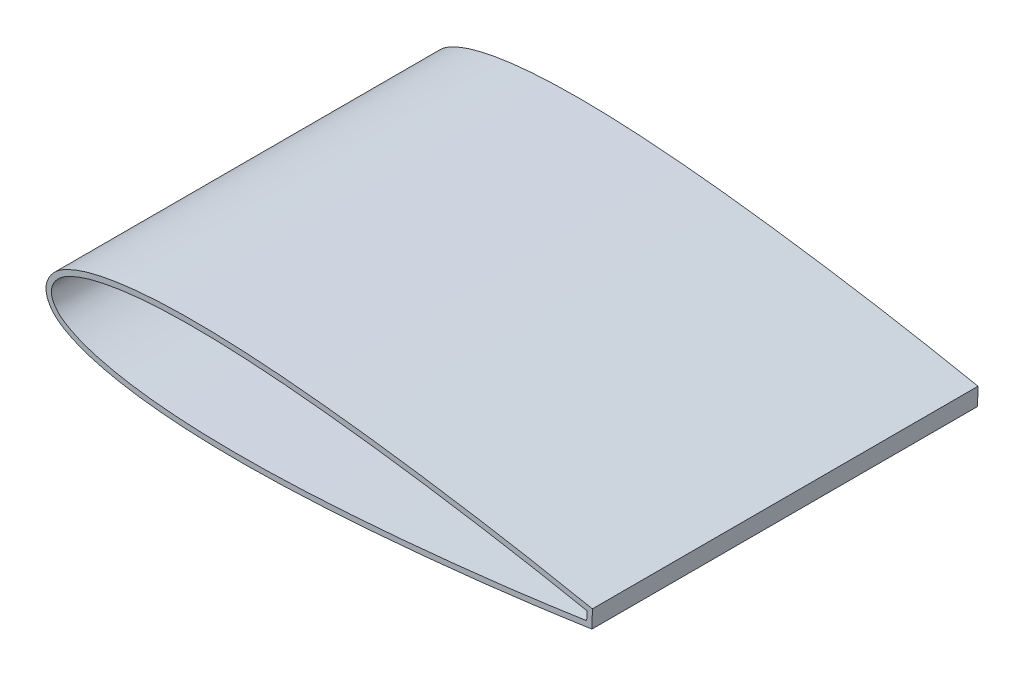
SolidWorks part; units mm, degrees
ref_plane "Alzado" through (0, 0, 0) normal (0, 0, 1) x (1, 0, 0)
ref_plane "Planta" through (0, 0, 0) normal (0, 1, 0) x (1, 0, 0)
ref_plane "Vista lateral" through (0, 0, 0) normal (1, 0, 0) x (0, 0, -1)
sketch "Croquis1" plane through (0, 0, 0) normal (0, 0, 1) x (1, 0, 0)
  line L1 (99.9588, -3.4209) -> (100, -1.7831)
  line L2 (100.9372, -4.2884) -> (101.0209, -0.9659)
  spline S0 degree 1 poles (101.0209, -0.9659) (100.9372, -4.2884) knots 0 0 1 1 construction
  spline S1 degree 3 poles (101.0209, -0.9659) (96.8153, -0.1329) (88.3989, 1.4983) (75.7013, 3.6191) (65.0923, 5.1744) (56.5758, 6.2611) (50.173, 6.9817) (43.7516, 7.5934) (37.3088, 8.062) (30.8435, 8.3521) (25.4356, 8.4019) (21.0964, 8.2838) (17.8368, 8.0987) (14.5726, 7.7994) (11.3002, 7.3497) (8.5784, 6.8084) (6.3964, 6.2318) (4.7455, 5.683) (3.1251, 4.9883) (1.5028, 4.12) (0.07, 2.8356) (-0.7762, 1.3315) (-1.0992, -0.0572) (-0.8465, -1.4604) (-0.077, -3.0052) (1.2893, -4.3602) (2.8658, -5.3089) (4.4492, -6.0843) (6.0704, -6.7154) (8.2207, -7.4011) (10.9117, -8.0788) (14.1574, -8.6925) (17.4024, -9.1557) (20.6486, -9.5046) (24.9763, -9.8409) (30.3799, -10.0633) (36.8516, -10.0989) (43.3098, -9.9551) (49.7538, -9.6673) (56.1848, -9.2698) (64.7452, -8.6131) (75.419, -7.5936) (88.2073, -6.1144) (96.6951, -4.9088) (100.9372, -4.2884) knots -0.007442 -0.007442 -0.007442 -0.007442 0.055988 0.119418 0.182849 0.214564 0.246279 0.277994 0.309709 0.341424 0.373139 0.388997 0.404855 0.420712 0.43657 0.452427 0.460356 0.468285 0.476214 0.484142 0.492071 0.496036 0.5 0.503964 0.507929 0.515858 0.523786 0.531715 0.539644 0.547573 0.56343 0.579288 0.595145 0.611003 0.626861 0.658576 0.690291 0.722006 0.753721 0.785436 0.817151 0.880582 0.944012 1.007442 1.007442 1.007442 1.007442
  spline S2 degree 3 poles (100, -1.7831) (95.8344, -0.958) (87.4933, 0.643) (74.9228, 2.7277) (62.3137, 4.5641) (49.6569, 6.0848) (39.0603, 6.9894) (30.5507, 7.3591) (24.1546, 7.4079) (18.8173, 7.1888) (14.5521, 6.79) (11.3582, 6.3445) (8.1856, 5.7066) (5.564, 4.9488) (3.5111, 4.0637) (2.0419, 3.2637) (0.599, 1.9526) (-0.279, -0.0779) (0.4957, -2.1499) (1.8708, -3.5321) (3.2979, -4.4049) (5.3036, -5.3922) (7.8838, -6.281) (11.0203, -7.0778) (14.1877, -7.6833) (18.4274, -8.2963) (23.747, -8.7837) (30.1374, -9.0568) (38.6548, -9.1158) (49.2835, -8.7455) (62.0009, -7.8637) (74.6864, -6.6642) (87.3459, -5.2146) (95.757, -4.0353) (99.9588, -3.4209) knots -0.003281 -0.003281 -0.003281 -0.003281 0.059629 0.122539 0.185449 0.24836 0.31127 0.342725 0.37418 0.405635 0.421362 0.43709 0.452817 0.468545 0.476409 0.484272 0.492136 0.5 0.507864 0.515728 0.523591 0.531455 0.547183 0.56291 0.578638 0.594365 0.62582 0.657275 0.68873 0.75164 0.814551 0.877461 0.940371 1.003281 1.003281 1.003281 1.003281
  dimension "D2" = 1
  dimension "D1" = 100
extrude "Saliente-Extruir1" add sketch "Croquis1" along normal blind 70
sketch "Croquis2" plane through (0, 0, 70) normal (0, 0, 1) x (1, 0, 0)
  line L0 (6.9696, 5.3388) -> (4.7355, 13.1426) construction
  line L1 (13.0976, 6.5801) -> (12.1874, 13.1292) construction
  line L2 (19.3249, 7.1769) -> (18.9088, 14.1748) construction
  line L3 (25.5786, 7.3722) -> (25.5327, 14.7723) construction
  line L4 (31.835, 7.2836) -> (32.0458, 13.7556) construction
  line L5 (38.085, 6.9832) -> (38.5713, 14.7812) construction
  line L6 (44.3249, 6.5168) -> (44.9854, 14.1724) construction
  line L7 (50.5535, 5.918) -> (51.1744, 11.8208) construction
  line L8 (56.7712, 5.2143) -> (57.5908, 11.9985) construction
  line L9 (62.9782, 4.4217) -> (63.8478, 10.901) construction
  line L10 (69.175, 3.5529) -> (70.2993, 11.2554) construction
  line L11 (75.362, 2.6168) -> (76.4898, 9.8261) construction
  line L12 (81.5391, 1.618) -> (82.5894, 7.9004) construction
  line L13 (87.7048, 0.5506) -> (88.9057, 7.2473) construction
  line L14 (93.275, -0.4778) -> (94.3912, 5.4138) construction
  line L15 (93.7641, -4.305) -> (94.4573, -9.3042) construction
  line L16 (87.5617, -5.1329) -> (88.3084, -10.9765) construction
  line L17 (81.3501, -5.8888) -> (81.9821, -11.3457) construction
  line L18 (75.1305, -6.5754) -> (75.5961, -10.9995) construction
  line L19 (68.9043, -7.1991) -> (69.4026, -12.4508) construction
  line L20 (62.6716, -7.7549) -> (63.088, -12.7548) construction
  line L21 (56.4326, -8.2342) -> (56.8686, -14.4627) construction
  line L22 (50.1874, -8.6241) -> (50.5085, -14.5151) construction
  line L23 (43.9365, -8.9087) -> (44.1623, -15.2248) construction
  line L24 (37.6811, -9.0605) -> (37.7711, -16.6006) construction
  line L25 (31.4239, -9.0461) -> (31.2647, -17.995) construction
  line L26 (25.1709, -8.8197) -> (24.6283, -18.4061) construction
  line L27 (18.935, -8.31) -> (17.9505, -17.2458) construction
  line L28 (12.7457, -7.4005) -> (10.6255, -18.5177) construction
  line L29 (6.6879, -5.8524) -> (3.2835, -15.8184) construction
  line L30 (1.247, -2.8692) -> (-5.2779, -9.0949) construction
  line L31 (0, 0) -> (-9.3368, 0.5427)
  line L32 (1.3855, 2.6331) -> (-4.9918, 9.3628) construction
  spline S0 degree 3 poles (1410.1565, 3729.758) (505.9884, -229.8774) (307.0725, -35.7726) (74.9228, 2.7277) (62.3137, 4.5641) (49.6569, 6.0848) (39.0603, 6.9894) (30.5507, 7.3591) (24.1546, 7.4079) (18.8173, 7.1888) (14.5521, 6.79) (11.3582, 6.3445) (8.1856, 5.7066) (5.564, 4.9488) (3.5111, 4.0637) (2.0419, 3.2637) (0.599, 1.9526) (-0.279, -0.0779) (0.4957, -2.1499) (1.8708, -3.5321) (3.2979, -4.4049) (5.3036, -5.3922) (7.8838, -6.281) (11.0203, -7.0778) (14.1877, -7.6833) (18.4274, -8.2963) (23.747, -8.7837) (30.1374, -9.0568) (38.6548, -9.1158) (49.2835, -8.7455) (62.0009, -7.8637) (74.6864, -6.6642) (308.4796, 20.1055) (516.9112, 203.9553) (1220.6847, -3796.1795) knots -3.299985 -3.299985 -3.299985 -3.299985 0.059629 0.122539 0.185449 0.24836 0.31127 0.342725 0.37418 0.405635 0.421362 0.43709 0.452817 0.468545 0.476409 0.484272 0.492136 0.5 0.507864 0.515728 0.523591 0.531455 0.547183 0.56291 0.578638 0.594365 0.62582 0.657275 0.68873 0.75164 0.814551 0.877461 0.940371 4.29999 4.29999 4.29999 4.29999 only from (100, -1.7831) to (99.9588, -3.4209) construction
  spline S1 degree 3 poles (100, -1.7831) (95.8344, -0.958) (87.4933, 0.643) (74.9228, 2.7277) (62.3137, 4.5641) (49.6569, 6.0848) (39.0603, 6.9894) (30.5507, 7.3591) (24.1546, 7.4079) (18.8173, 7.1888) (14.5521, 6.79) (11.3582, 6.3445) (8.1856, 5.7066) (5.564, 4.9488) (3.5111, 4.0637) (2.0419, 3.2637) (0.599, 1.9526) (-0.279, -0.0779) (0.4957, -2.1499) (1.8708, -3.5321) (3.2979, -4.4049) (5.3036, -5.3922) (7.8838, -6.281) (11.0203, -7.0778) (14.1877, -7.6833) (18.4274, -8.2963) (23.747, -8.7837) (30.1374, -9.0568) (38.6548, -9.1158) (49.2835, -8.7455) (62.0009, -7.8637) (74.6864, -6.6642) (87.3459, -5.2146) (95.757, -4.0353) (99.9588, -3.4209) knots -0.003281 -0.003281 -0.003281 -0.003281 0.059629 0.122539 0.185449 0.24836 0.31127 0.342725 0.37418 0.405635 0.421362 0.43709 0.452817 0.468545 0.476409 0.484272 0.492136 0.5 0.507864 0.515728 0.523591 0.531455 0.547183 0.56291 0.578638 0.594365 0.62582 0.657275 0.68873 0.75164 0.814551 0.877461 0.940371 1.003281 1.003281 1.003281 1.003281 construction
  point P3 (93.8577, -0.5885)
  point P4 (87.7048, 0.5506)
  point P5 (81.5391, 1.618)
  point P6 (75.362, 2.6168)
  point P7 (69.175, 3.5529)
  point P8 (62.9782, 4.4217)
  point P9 (56.7712, 5.2143)
  point P10 (50.5535, 5.918)
  point P11 (44.3249, 6.5168)
  point P12 (38.085, 6.9832)
  point P13 (31.835, 7.2836)
  point P14 (25.5786, 7.3722)
  point P15 (19.3249, 7.1769)
  point P16 (13.0976, 6.5801)
  point P17 (6.9696, 5.3388)
  point P18 (1.3855, 2.6331)
  point P19 (1.247, -2.8692)
  point P20 (6.6879, -5.8524)
  point P21 (12.7457, -7.4005)
  point P22 (18.935, -8.31)
  point P23 (25.1709, -8.8197)
  point P24 (31.4239, -9.0461)
  point P25 (37.6811, -9.0605)
  point P26 (43.9365, -8.9087)
  point P27 (50.1874, -8.6241)
  point P28 (56.4326, -8.2342)
  point P29 (62.6716, -7.7549)
  point P30 (68.9043, -7.1991)
  point P31 (75.1305, -6.5754)
  point P32 (81.3501, -5.8888)
  point P33 (87.5617, -5.1329)
  point P34 (93.7641, -4.305)
sketch "Croquis4" plane through (0, 0, 0) normal (0, 0, -1) x (-1, 0, 0)
  line L0 (-100.9372, -4.2884) -> (-101.0209, -0.9659) construction
  line L1 (-100.9372, -4.2884) -> (-101.0209, -0.9659)
  spline S0 degree 3 poles (-1054.9434, 1734.0373) (-393.052, -136.0137) (-245.8608, -24.8016) (-75.7013, 3.6191) (-65.0923, 5.1744) (-56.5758, 6.2611) (-50.173, 6.9817) (-43.7516, 7.5934) (-37.3088, 8.062) (-30.8435, 8.3521) (-25.4356, 8.4019) (-21.0964, 8.2838) (-17.8368, 8.0987) (-14.5726, 7.7994) (-11.3002, 7.3497) (-8.5784, 6.8084) (-6.3964, 6.2318) (-4.7455, 5.683) (-3.1251, 4.9883) (-1.5028, 4.12) (-0.07, 2.8356) (0.7762, 1.3315) (1.0992, -0.0572) (0.8465, -1.4604) (0.077, -3.0052) (-1.2893, -4.3602) (-2.8658, -5.3089) (-4.4492, -6.0843) (-6.0704, -6.7154) (-8.2207, -7.4011) (-10.9117, -8.0788) (-14.1574, -8.6925) (-17.4024, -9.1557) (-20.6486, -9.5046) (-24.9763, -9.8409) (-30.3799, -10.0633) (-36.8516, -10.0989) (-43.3098, -9.9551) (-49.7538, -9.6673) (-56.1848, -9.2698) (-64.7452, -8.6131) (-75.419, -7.5936) (-246.793, 12.2286) (-399.394, 115.893) (-966.3441, -1785.0939) knots -2.36721 -2.36721 -2.36721 -2.36721 0.055988 0.119418 0.182849 0.214564 0.246279 0.277994 0.309709 0.341424 0.373139 0.388997 0.404855 0.420712 0.43657 0.452427 0.460356 0.468285 0.476214 0.484142 0.492071 0.496036 0.5 0.503964 0.507929 0.515858 0.523786 0.531715 0.539644 0.547573 0.56343 0.579288 0.595145 0.611003 0.626861 0.658576 0.690291 0.722006 0.753721 0.785436 0.817151 0.880582 0.944012 3.367209 3.367209 3.367209 3.367209 only from (-101.0209, -0.9659) to (-100.9372, -4.2884) construction
  spline S1 degree 3 poles (-101.0209, -0.9659) (-96.8153, -0.1329) (-88.3989, 1.4983) (-75.7013, 3.6191) (-65.0923, 5.1744) (-56.5758, 6.2611) (-50.173, 6.9817) (-43.7516, 7.5934) (-37.3088, 8.062) (-30.8435, 8.3521) (-25.4356, 8.4019) (-21.0964, 8.2838) (-17.8368, 8.0987) (-14.5726, 7.7994) (-11.3002, 7.3497) (-8.5784, 6.8084) (-6.3964, 6.2318) (-4.7455, 5.683) (-3.1251, 4.9883) (-1.5028, 4.12) (-0.07, 2.8356) (0.7762, 1.3315) (1.0992, -0.0572) (0.8465, -1.4604) (0.077, -3.0052) (-1.2893, -4.3602) (-2.8658, -5.3089) (-4.4492, -6.0843) (-6.0704, -6.7154) (-8.2207, -7.4011) (-10.9117, -8.0788) (-14.1574, -8.6925) (-17.4024, -9.1557) (-20.6486, -9.5046) (-24.9763, -9.8409) (-30.3799, -10.0633) (-36.8516, -10.0989) (-43.3098, -9.9551) (-49.7538, -9.6673) (-56.1848, -9.2698) (-64.7452, -8.6131) (-75.419, -7.5936) (-88.2073, -6.1144) (-96.6951, -4.9088) (-100.9372, -4.2884) knots -0.007442 -0.007442 -0.007442 -0.007442 0.055988 0.119418 0.182849 0.214564 0.246279 0.277994 0.309709 0.341424 0.373139 0.388997 0.404855 0.420712 0.43657 0.452427 0.460356 0.468285 0.476214 0.484142 0.492071 0.496036 0.5 0.503964 0.507929 0.515858 0.523786 0.531715 0.539644 0.547573 0.56343 0.579288 0.595145 0.611003 0.626861 0.658576 0.690291 0.722006 0.753721 0.785436 0.817151 0.880582 0.944012 1.007442 1.007442 1.007442 1.007442
extrude "Saliente-Extruir2" add sketch "Croquis4" along normal blind 2
